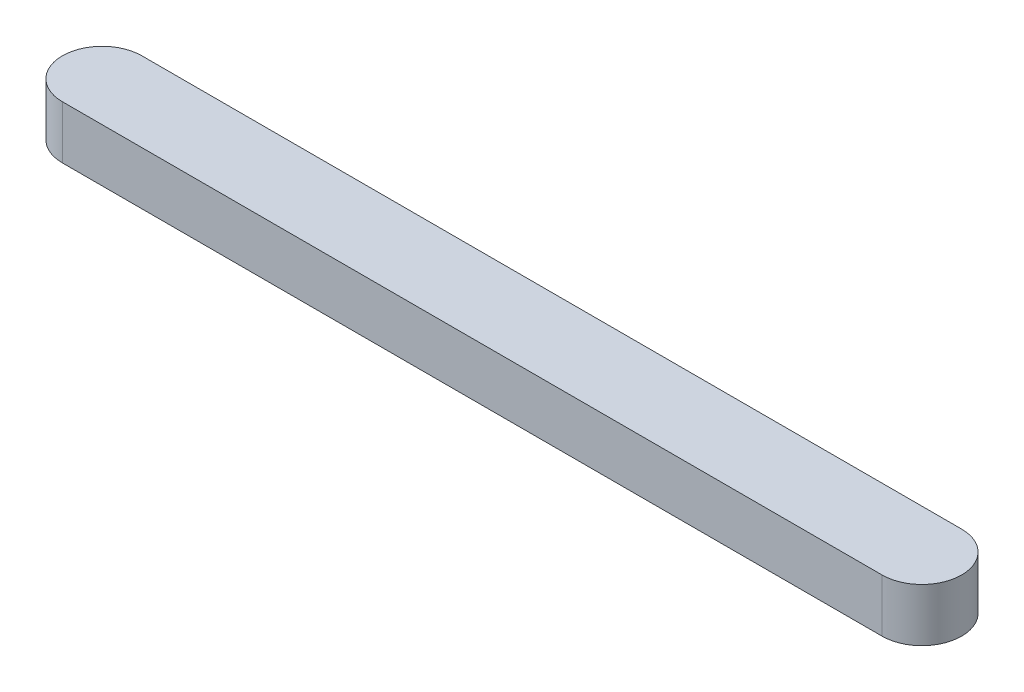
SolidWorks part; units mm, degrees
ref_plane "Front Plane" through (0, 0, 0) normal (0, 0, 1) x (1, 0, 0)
ref_plane "Top Plane" through (0, 0, 0) normal (0, 1, 0) x (1, 0, 0)
ref_plane "Right Plane" through (0, 0, 0) normal (1, 0, 0) x (0, 0, -1)
sketch "Sketch1" plane through (0, 0, 0) normal (0, 1, 0) x (1, 0, 0)
  line L0 (-30.925, 0) -> (30.925, 0) construction
  line L1 (-30.925, 3) -> (30.925, 3)
  line L2 (-30.925, -3) -> (30.925, -3)
  arc A0 (-30.925, 3) -> (-30.925, -3) centre (-30.925, 0) ccw
  arc A1 (30.925, -3) -> (30.925, 3) centre (30.925, 0) ccw
  point P2 (0, 0)
  point P8 (0, 0)
  dimension "D2" = 3
  dimension "D1" = 61.85
extrude "Boss-Extrude1" add sketch "Sketch1" along normal blind 4
